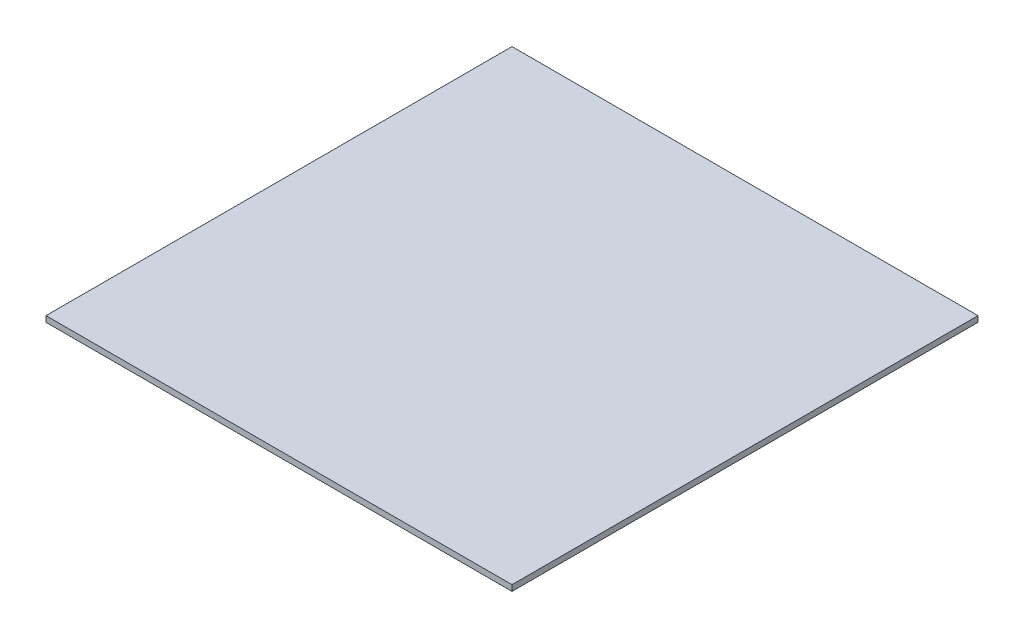
SolidWorks part; units mm, degrees
ref_plane "Front Plane" through (0, 0, 0) normal (0, 0, 1) x (1, 0, 0)
ref_plane "Top Plane" through (0, 0, 0) normal (0, 1, 0) x (1, 0, 0)
ref_plane "Right Plane" through (0, 0, 0) normal (1, 0, 0) x (0, 0, -1)
sketch "Sketch1" plane through (0, 0, 0) normal (0, 1, 0) x (1, 0, 0)
  line L1 (-127, -127) -> (127, -127)
  line L2 (-127, -127) -> (-127, 127)
  line L3 (-127, 127) -> (127, 127)
  line L4 (127, -127) -> (127, 127)
  line L5 (-127, -127) -> (127, 127) construction
  line L6 (-127, 127) -> (127, -127) construction
  point P0 (0, 0)
  dimension "D1" = 254
  dimension "D2" = 254
extrude "Boss-Extrude1" add sketch "Sketch1" along normal blind 3.175
